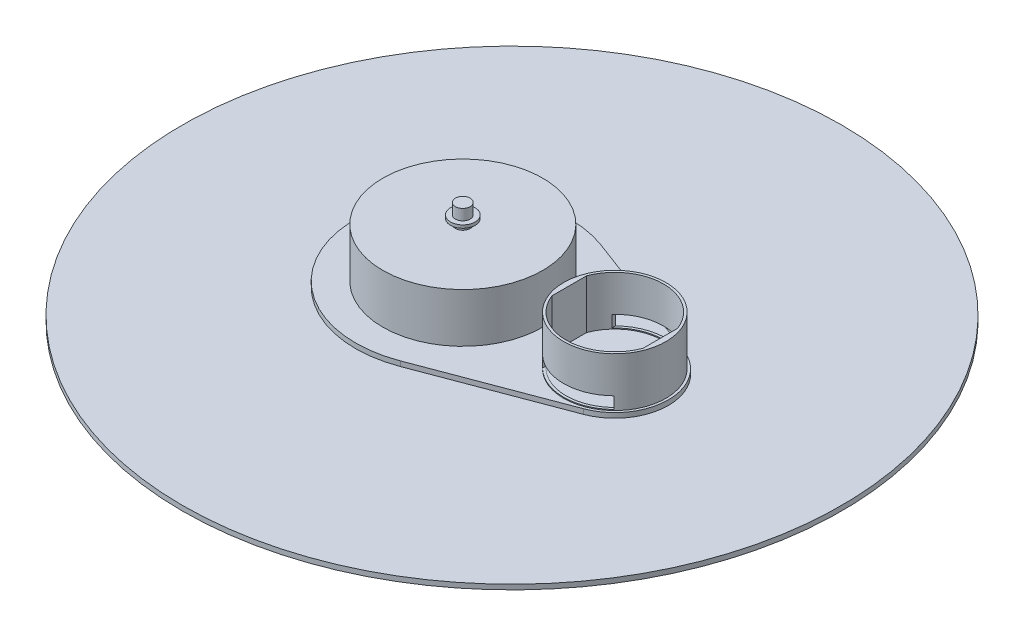
SolidWorks part; units mm, degrees
ref_plane "前视基准面" through (0, 0, 0) normal (0, 0, 1) x (1, 0, 0)
ref_plane "上视基准面" through (0, 0, 0) normal (0, 1, 0) x (1, 0, 0)
ref_plane "右视基准面" through (0, 0, 0) normal (1, 0, 0) x (0, 0, -1)
other "Configuration Table"
sketch "草图1" plane through (0, 0, 0) normal (0, 1, 0) x (1, 0, 0)
  line L0 (0, 0) -> (318, 0) construction
  line L1 (0, 0) -> (0, 124.8405) construction
  line L2 (109, 0) -> (109, 124.8405) construction
  line L3 (263.5, 0) -> (263.5, 117.7973) construction
  line L4 (318, 0) -> (318, 117.7973) construction
  line L5 (147.4498, 101.9932) -> (282.7249, 50.9966)
  line L6 (147.4498, -101.9932) -> (282.7249, -50.9966)
  arc A0 (282.7249, -50.9966) -> (263.5, 54.5) centre (263.5, 0) ccw
  arc A1 (147.4498, 101.9932) -> (147.4498, -101.9932) centre (109, 0) ccw
  dimension "D4" = 109
  dimension "D5" = 218
  dimension "D1" = 318
  dimension "D2" = 54.5
  dimension "D3" = 109
extrude "凸台-拉伸1" add sketch "草图1" along normal blind 5
ref_plane "基准面1" through (0, 5, 0) normal (0, 1, 0) x (1, 0, 0)
sketch "草图2" plane through (0, 5, 0) normal (0, 1, 0) x (1, 0, 0)
  line L0 (0, 0) -> (318, 0) construction
  line L1 (318, 0) -> (318, 65.2559) construction
  line L2 (263.5, 0) -> (263.5, 71.8372) construction
  line L3 (217.25, 17.6405) -> (217.25, -17.6405)
  line L4 (309.75, 17.6405) -> (309.75, -17.6405)
  arc A0 (282.7249, -50.9966) -> (282.7249, 50.9966) centre (263.5, 0) ccw construction
  arc A1 (217.25, -17.6405) -> (309.75, -17.6405) centre (263.5, 0) ccw
  circle A2 centre (263.5, 0) radius 52
  arc A3 (309.75, 17.6405) -> (217.25, 17.6405) centre (263.5, 0) ccw
  dimension "D2" = 99
  dimension "D3" = 104
  dimension "D1" = 54.5
  dimension "D4" = 92.5
extrude "凸台-拉伸2" add sketch "草图2" along normal blind 50
sketch "草图3" plane through (0, 5, 0) normal (0, 1, 0) x (1, 0, 0)
  line L0 (0, 0) -> (318, 0) construction
  line L1 (109, 21.0849) -> (109, 0) construction
  arc A0 (282.7249, -50.9966) -> (282.7249, 50.9966) centre (263.5, 0) ccw construction
  circle A1 centre (109, 0) radius 7.5
  dimension "D2" = 15
  dimension "D1" = 109
extrude "凸台-拉伸3" add sketch "草图3" along normal blind 55.3
ref_plane "基准面2" through (0, 60.3, 0) normal (0, 1, 0) x (1, 0, 0)
sketch "草图4" plane through (0, 60.3, 0) normal (0, 1, 0) x (1, 0, 0)
  line L0 (101.5, 0) -> (116.5, 0) construction
  line L1 (109, 7.5) -> (109, -7.5) construction
  line L2 (109, 0) -> (121.5, 0)
  circle A0 centre (109, 0) radius 7.5 construction
  circle A1 centre (109, 0) radius 7.5 construction
  circle A2 centre (109, 0) radius 12.5
  dimension "D1" = 25
extrude "凸台-拉伸4" add sketch "草图4" along normal blind 3
ref_plane "基准面3" through (0, 63.3, 0) normal (0, 1, 0) x (1, 0, 0)
sketch "草图5" plane through (0, 63.3, 0) normal (0, 1, 0) x (1, 0, 0)
  line L0 (96.5, 0) -> (121.5, 0) construction
  circle A0 centre (109, 0) radius 12.5 construction
  circle A1 centre (109, 0) radius 7.5
  dimension "D1" = 15
extrude "凸台-拉伸5" add sketch "草图5" along normal blind 11
sketch "草图6" plane through (0, 5, 0) normal (0, 1, 0) x (1, 0, 0)
  circle A0 centre (109, 0) radius 81.2756
extrude "凸台-拉伸6" add sketch "草图6" along normal blind 50
ref_plane "基准面4" through (0, 0, 0) normal (0, -1, 0) x (-1, 0, 0)
sketch "草图7" plane through (0, 0, 0) normal (0, -1, 0) x (-1, 0, 0)
  line L0 (-318, 0) -> (0, 0)
  arc A0 (-282.7249, 50.9966) -> (-282.7249, -50.9966) centre (-263.5, 0) ccw construction
  circle A1 centre (-159, 0) radius 335
  dimension "D1" = 670
extrude "凸台-拉伸7" add sketch "草图7" along normal blind 5
ref_plane "基准面5" through (0, 0, 52) normal (0, 0, 1) x (1, 0, 0)
sketch "草图8" plane through (0, 0, 52) normal (0, 0, 1) x (1, 0, 0)
  line L0 (263.5, 55) -> (263.5, 19.0222) construction
  line L2 (227.0901, 6) -> (299.9099, 6)
  line L3 (299.9099, 6) -> (299.9099, 18)
  line L4 (299.9099, 18) -> (227.0901, 18)
  line L5 (227.0901, 18) -> (227.0901, 6)
  line L6 (119.9, 5) -> (-119.9, 5) construction
  dimension "D1" = 1
  dimension "D2" = 12
extrude "切除-拉伸1" cut sketch "草图8" against normal through all both and the other way through all
